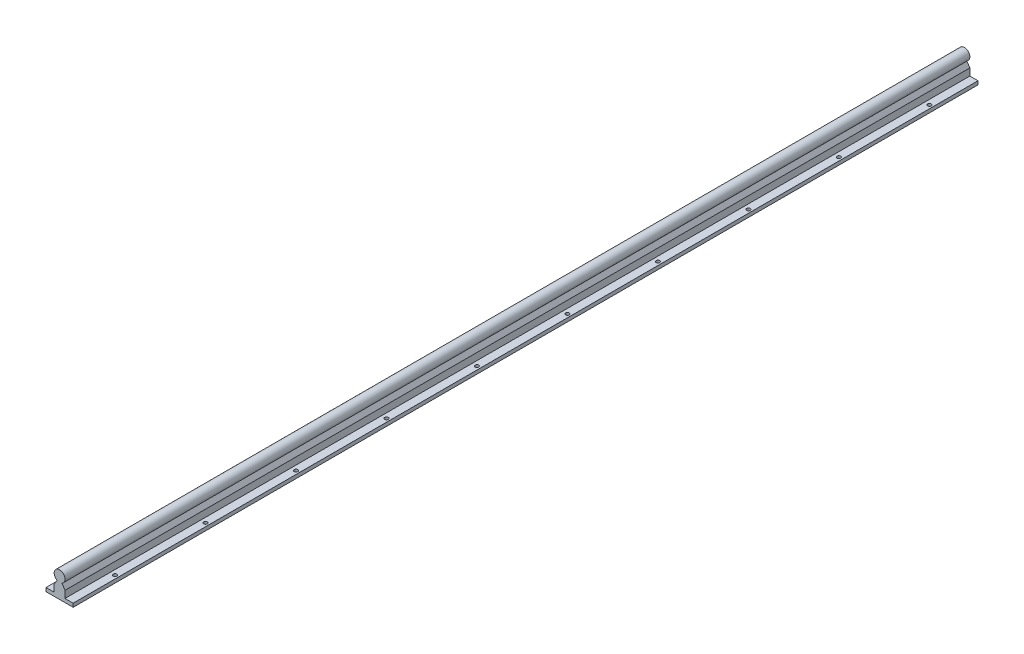
SolidWorks part; units mm, degrees
material "Chrome Stainless Steel"
ref_plane "Front Plane" through (0, 0, 0) normal (0, 0, 1) x (1, 0, 0)
ref_plane "Top Plane" through (0, 0, 0) normal (0, 1, 0) x (1, 0, 0)
ref_plane "Right Plane" through (0, 0, 0) normal (1, 0, 0) x (0, 0, -1)
sketch "Sketch1" plane through (0, 0, 0) normal (0, 0, 1) x (1, 0, 0)
  line L0 (19.7075, 0) -> (-10.2925, 0)
  line L1 (19.7075, 0) -> (19.7075, 4)
  line L2 (19.7075, 4) -> (10.7075, 4)
  line L3 (10.7075, 4) -> (10.7075, 11.8)
  line L4 (7.3075, 17) -> (10.7075, 11.8)
  line L5 (-1.2925, 11.8) -> (2.1075, 17)
  line L6 (4.7075, 2) -> (4.7075, 38.0795) construction
  line L9 (-1.2925, 4) -> (-1.2925, 11.8)
  line L10 (-10.2925, 0) -> (-10.2925, 4)
  line L11 (-10.2925, 4) -> (-1.2925, 4)
  arc A0 (7.3075, 17) -> (2.1075, 17) centre (4.7075, 22.4074) ccw
  point P17 (4.7075, 0)
  dimension "D5" = 6
  dimension "D1" = 15
  dimension "D2" = 4
  dimension "D4" = 17
  dimension "D6" = 2.6
  dimension "D8" = 22.4074
  dimension "D9" = 6
extrude "Boss-Extrude1" add sketch "Sketch1" along normal blind 1000
sketch "Sketch2" plane through (0, 4, 0) normal (0, 1, 0) x (1, 0, 0)
  line L0 (-1.2925, 0) -> (-10.2925, 0) construction
  line L1 (-10.2925, -1000) -> (-10.2925, 0) construction
  line L2 (19.7075, -1000) -> (19.7075, 0) construction
  circle A0 centre (-6.5425, -50) radius 2
  circle A1 centre (-6.5425, -150) radius 2
  circle A2 centre (-6.5425, -250) radius 2
  circle A3 centre (-6.5425, -350) radius 2
  circle A4 centre (-6.5425, -450) radius 2
  circle A5 centre (-6.5425, -550) radius 2
  circle A6 centre (-6.5425, -650) radius 2
  circle A7 centre (-6.5425, -750) radius 2
  circle A8 centre (-6.5425, -850) radius 2
  circle A9 centre (-6.5425, -950) radius 2
  circle A10 centre (15.9575, -50) radius 2
  circle A11 centre (15.9575, -150) radius 2
  circle A12 centre (15.9575, -250) radius 2
  circle A13 centre (15.9575, -350) radius 2
  circle A14 centre (15.9575, -450) radius 2
  circle A15 centre (15.9575, -550) radius 2
  circle A16 centre (15.9575, -650) radius 2
  circle A17 centre (15.9575, -750) radius 2
  circle A18 centre (15.9575, -850) radius 2
  circle A19 centre (15.9575, -950) radius 2
  dimension "D1" = 50
  dimension "D3" = 3.75
  dimension "D4" = 3.75
  dimension "D5" = 22.5
  dimension "D2" = 10
extrude "Cut-Extrude1" cut sketch "Sketch2" against normal up to next
